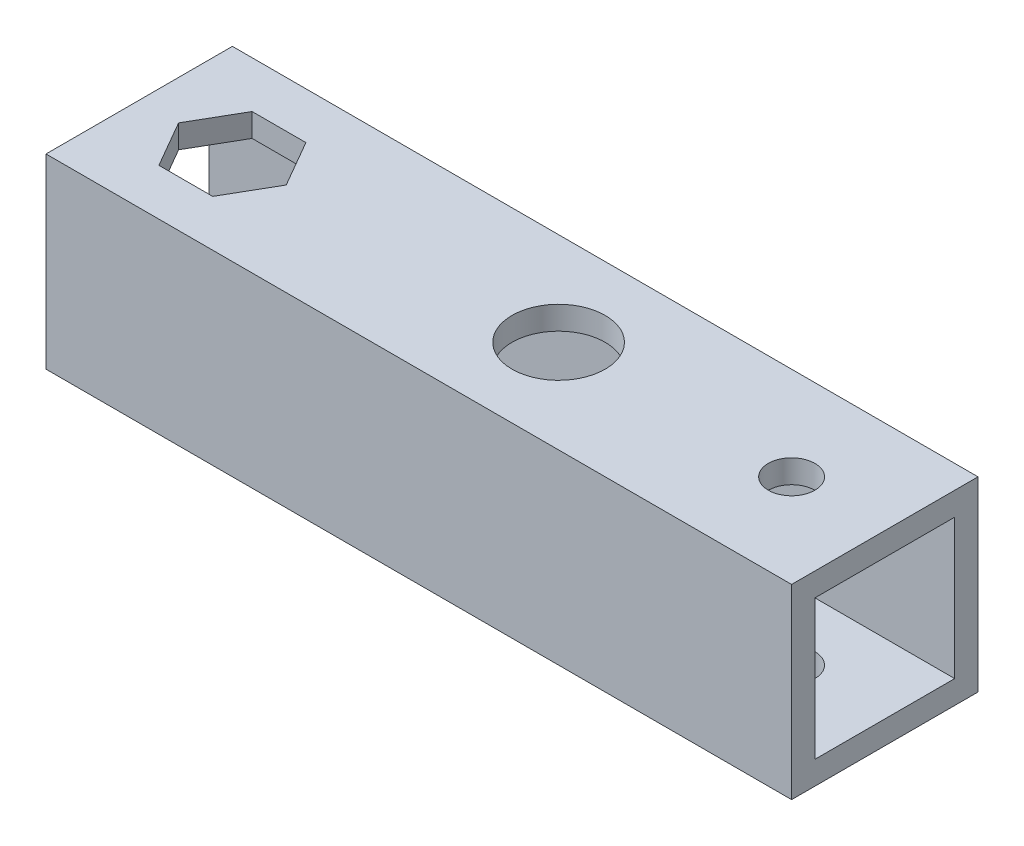
SolidWorks part; units mm, degrees
ref_plane "Front Plane" through (0, 0, 0) normal (0, 0, 1) x (1, 0, 0)
ref_plane "Top Plane" through (0, 0, 0) normal (0, 1, 0) x (1, 0, 0)
ref_plane "Right Plane" through (0, 0, 0) normal (1, 0, 0) x (0, 0, -1)
sketch "Sketch1" plane through (0, 0, 0) normal (0, 1, 0) x (1, 0, 0)
  line L1 (88.9, 12.7) -> (-12.7, 12.7)
  line L2 (88.9, 12.7) -> (88.9, -12.7)
  line L3 (88.9, -12.7) -> (-12.7, -12.7)
  line L4 (-12.7, 12.7) -> (-12.7, -12.7)
  line L5 (7.3323, 0) -> (3.6662, 6.35)
  line L6 (3.6662, 6.35) -> (-3.6662, 6.35)
  line L7 (-3.6662, 6.35) -> (-7.3323, 0)
  line L8 (-7.3323, 0) -> (-3.6662, -6.35)
  line L9 (-3.6662, -6.35) -> (3.6662, -6.35)
  line L10 (3.6662, -6.35) -> (7.3323, 0)
  circle A0 centre (0, 0) radius 6.35 construction
  circle A1 centre (44.45, 0) radius 6.35
  circle A2 centre (76.2, 0) radius 3.175
  circle A3 centre (0, 0) radius 6.35 construction
  dimension "D3" = 12.7
  dimension "D4" = 12.7
  dimension "D9" = 6.35
  dimension "D1" = 76.2
  dimension "D2" = 44.45
  dimension "D5" = 25.4
  dimension "D6" = 12.7
  dimension "D7" = 12.7
  dimension "D8" = 12.7
extrude "Boss-Extrude1" add sketch "Sketch1" along normal blind 25.4
sketch "Sketch2" plane through (88.9, 0, 0) normal (1, 0, 0) x (0, 0, -1)
  line L8 (-9.525, 3.175) -> (9.525, 3.175)
  line L9 (9.525, 3.175) -> (9.525, 22.225)
  line L10 (9.525, 22.225) -> (-9.525, 22.225)
  line L11 (-9.525, 22.225) -> (-9.525, 3.175)
  line L12 (-9.525, 3.175) -> (9.525, 3.175)
  line L13 (9.525, 3.175) -> (9.525, 22.225)
  line L14 (9.525, 22.225) -> (-9.525, 22.225)
  line L15 (-9.525, 22.225) -> (-9.525, 3.175)
  dimension "D1" = 3.175
extrude "Cut-Extrude1" cut sketch "Sketch2" against normal through all
